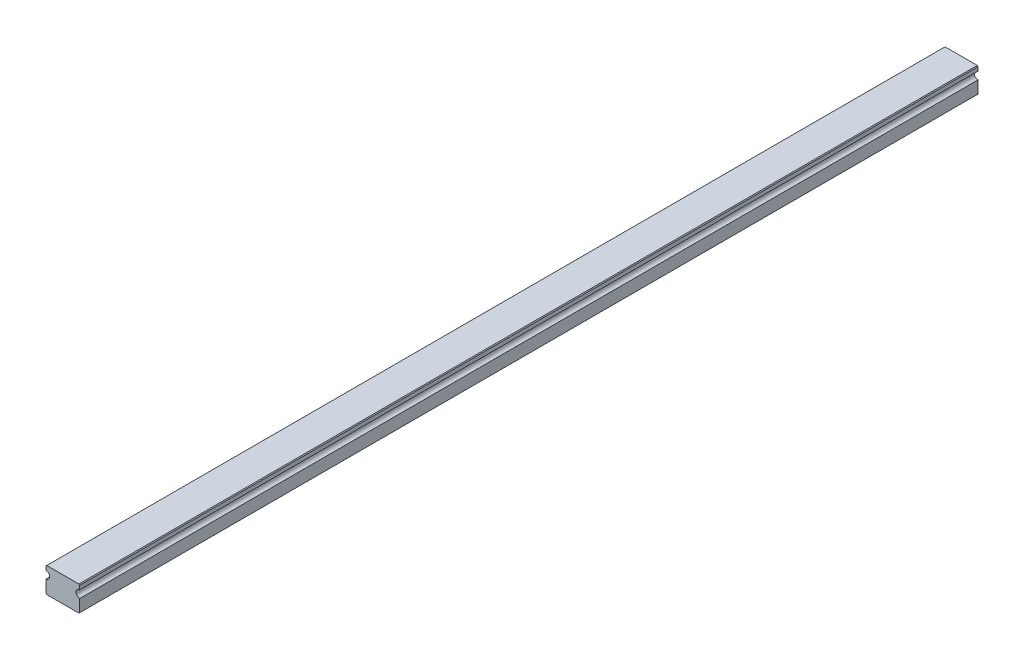
SolidWorks part; units mm, degrees
material "AISI 304"
ref_plane "前视基准面" through (0, 0, 0) normal (0, 0, 1) x (1, 0, 0)
ref_plane "上视基准面" through (0, 0, 0) normal (0, 1, 0) x (1, 0, 0)
ref_plane "右视基准面" through (0, 0, 0) normal (1, 0, 0) x (0, 0, -1)
sketch "Sketch1" plane through (0, 0, 0) normal (0, 0, 1) x (1, 0, 0)
  line L0 (-4.5, 0.1283) -> (-4.5, -3.1717)
  line L1 (-4.5, -3.1717) -> (-4.3, -3.3717)
  line L2 (-4.3, -3.3717) -> (4.3, -3.3717)
  line L4 (4.3, -3.3717) -> (4.5, -3.1717)
  line L5 (4.5, -3.1717) -> (4.5, 0.1283)
  line L6 (4.5, 2.1283) -> (4.5, 3.1717)
  line L7 (4.5, 3.1717) -> (4.3, 3.3717)
  line L8 (4.3, 3.3717) -> (-4.3, 3.3717)
  line L9 (-4.3, 3.3717) -> (-4.5, 3.1717)
  line L10 (-4.5, 3.1717) -> (-4.5, 2.1283)
  line L11 (0, -3.3717) -> (0, 3.3717) construction
  arc A0 (-4.5, 0.1283) -> (-3.5, 1.1283) centre (-4.5, 1.1283) ccw
  arc A2 (3.5, 1.1283) -> (4.5, 0.1283) centre (4.5, 1.1283) ccw
  arc A3 (4.5, 2.1283) -> (3.5, 1.1283) centre (4.5, 1.1283) ccw
  arc A4 (-3.5, 1.1283) -> (-4.5, 2.1283) centre (-4.5, 1.1283) ccw
  point P4 (0, 0)
extrude "Boss-Extrude1" add sketch "Sketch1" along normal mid plane 240
